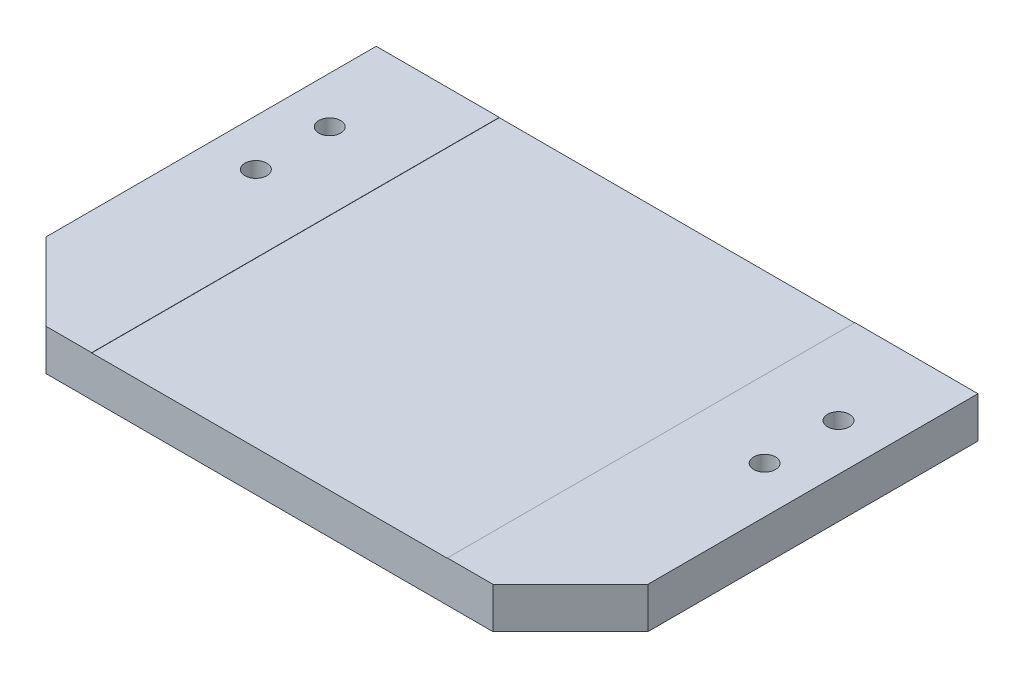
SolidWorks part; units mm, degrees
ref_plane "Plan de face" through (0, 0, 0) normal (0, 0, 1) x (1, 0, 0)
ref_plane "Plan de dessus" through (0, 0, 0) normal (0, 1, 0) x (1, 0, 0)
ref_plane "Plan de droite" through (0, 0, 0) normal (1, 0, 0) x (0, 0, -1)
sketch "Esquisse1" plane through (0, 0, 0) normal (0, 1, 0) x (1, 0, 0)
  line L0 (-11, 7.45) -> (11, 7.45)
  line L1 (11, 7.45) -> (11, -4.6216)
  line L2 (11, -4.6216) -> (8.1716, -7.45)
  line L3 (8.1716, -7.45) -> (-8.1716, -7.45)
  line L4 (-8.1716, -7.45) -> (-11, -4.6216)
  line L5 (-11, -4.6216) -> (-11, 7.45)
  line L6 (0, 7.45) -> (0, -7.45) construction
  circle A0 centre (-9.3, 1.35) radius 0.4
  circle A1 centre (-9.3, 4.05) radius 0.4
  circle A2 centre (9.3, 1.35) radius 0.4
  circle A3 centre (9.3, 4.05) radius 0.4
  point P8 (0, 0)
  point P9 (0, -7.45)
  point P19 (-9.3, 4.45)
  point P20 (-9.3, 0.95)
  point P21 (-9.7, 4.05)
  point P22 (9.7, 4.05)
  dimension "D7" = 0.8
  dimension "D8" = 0.8
  dimension "D9" = 0.8
  dimension "D10" = 0.8
  dimension "D1" = 14.9
  dimension "D2" = 22
  dimension "D3" = 4
  dimension "D4" = 4
  dimension "D5" = 135
  dimension "D6" = 135
  dimension "D11" = 3.5
  dimension "D12" = 3
  dimension "D13" = 1.3
  dimension "D14" = 1.3
extrude "Boss.-Extru.1" add sketch "Esquisse1" along normal blind 1.5
sketch "Esquisse2" plane through (0, 1.5, 0) normal (0, 1, 0) x (1, 0, 0)
  line L0 (11, 7.45) -> (-11, 7.45) construction
  line L1 (-6.5, 7.45) -> (6.5, 7.45)
  line L2 (-6.5, 7.45) -> (-6.5, -7.45)
  line L3 (-6.5, -7.45) -> (6.5, -7.45)
  line L4 (6.5, 7.45) -> (6.5, -7.45)
  line L5 (-8.1716, -7.45) -> (8.1716, -7.45) construction
  point P8 (0, 7.45)
  dimension "D1" = 13
extrude "Enlèv. mat.-Extru.1" cut sketch "Esquisse2" against normal blind 0.01
